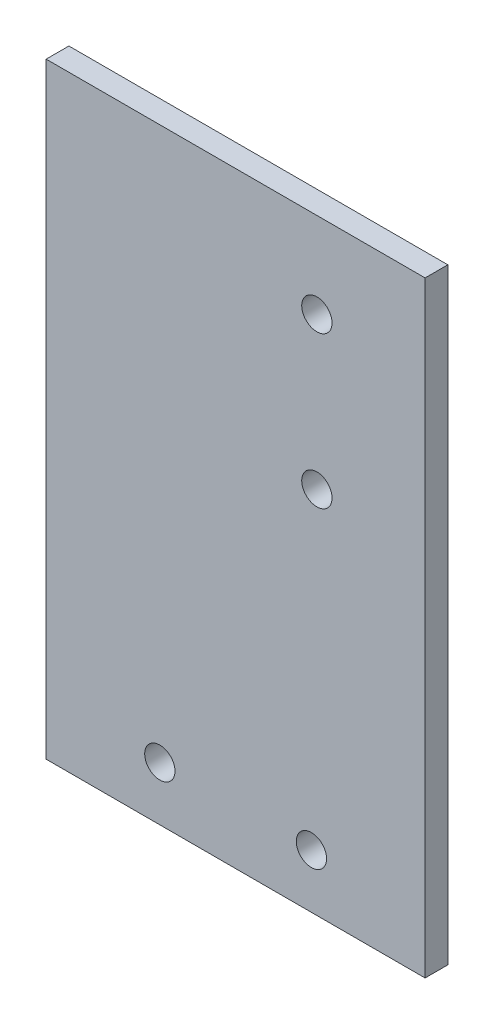
SolidWorks part; units mm, degrees
ref_plane "Front Plane" through (0, 0, 0) normal (0, 0, 1) x (1, 0, 0)
ref_plane "Top Plane" through (0, 0, 0) normal (0, 1, 0) x (1, 0, 0)
ref_plane "Right Plane" through (0, 0, 0) normal (1, 0, 0) x (0, 0, -1)
sketch "Sketch1" plane through (0, 0, 0) normal (0, 0, 1) x (1, 0, 0)
  line L0 (-25, 40) -> (-25, 0)
  line L1 (-25, 0) -> (0, 0)
  line L2 (0, 0) -> (0, 40)
  line L3 (0, 40) -> (-25, 40)
  circle A0 centre (-17.5, 3.56) radius 1
  circle A1 centre (-7.5, 3.56) radius 1
  circle A4 centre (-7.14, 34.35) radius 1
  circle A5 centre (-7.14, 24.35) radius 1
  dimension "D1" = 2
  dimension "D3" = 7.14
  dimension "D4" = 7.5
  dimension "D6" = 17.5
  dimension "D7" = 25
  dimension "D8" = 20.79
  dimension "D9" = 3.56
  dimension "D10" = 10
  dimension "D11" = 40
extrude "Boss-Extrude1" add sketch "Sketch1" along normal blind 1.5
